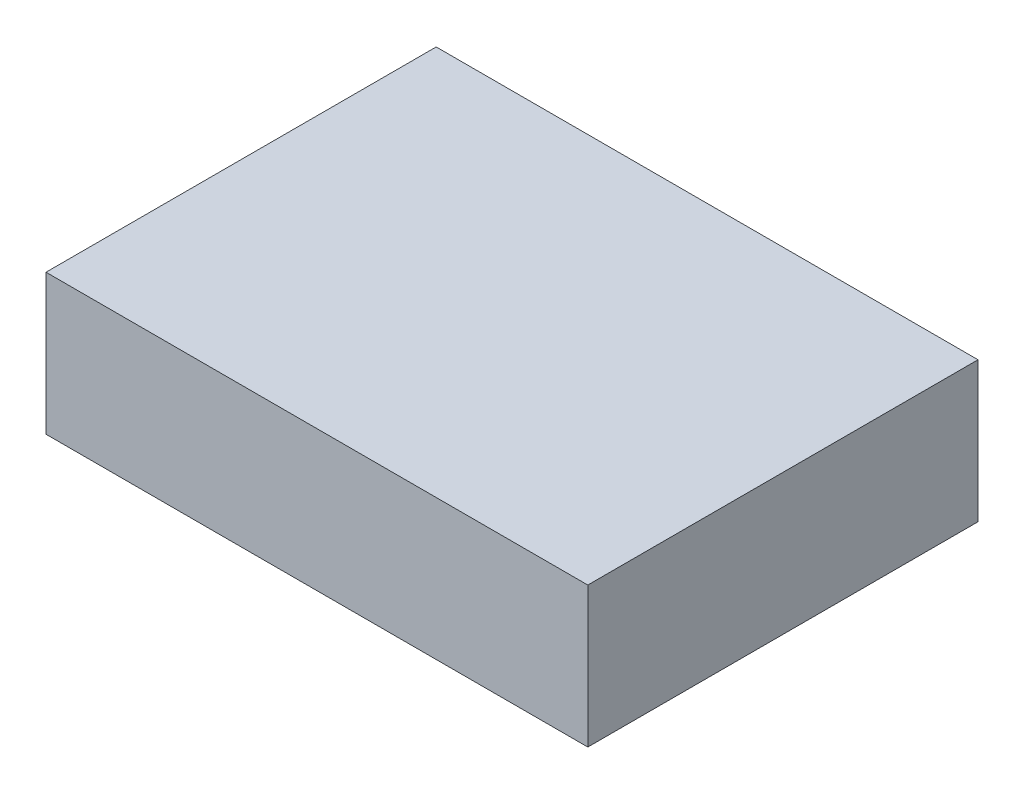
SolidWorks part; units mm, degrees
ref_plane "Front Plane" through (0, 0, 0) normal (0, 0, 1) x (1, 0, 0)
ref_plane "Top Plane" through (0, 0, 0) normal (0, 1, 0) x (1, 0, 0)
ref_plane "Right Plane" through (0, 0, 0) normal (1, 0, 0) x (0, 0, -1)
sketch "Sketch1" plane through (0, 0, 0) normal (0, 1, 0) x (1, 0, 0)
  line L1 (0, 0) -> (31.66, 0)
  line L2 (0, 0) -> (0, 22.8)
  line L3 (0, 22.8) -> (31.66, 22.8)
  line L4 (31.66, 0) -> (31.66, 22.8)
  dimension "D1" = 22.8
  dimension "D2" = 31.66
extrude "Boss-Extrude1" add sketch "Sketch1" along normal blind 8.2
